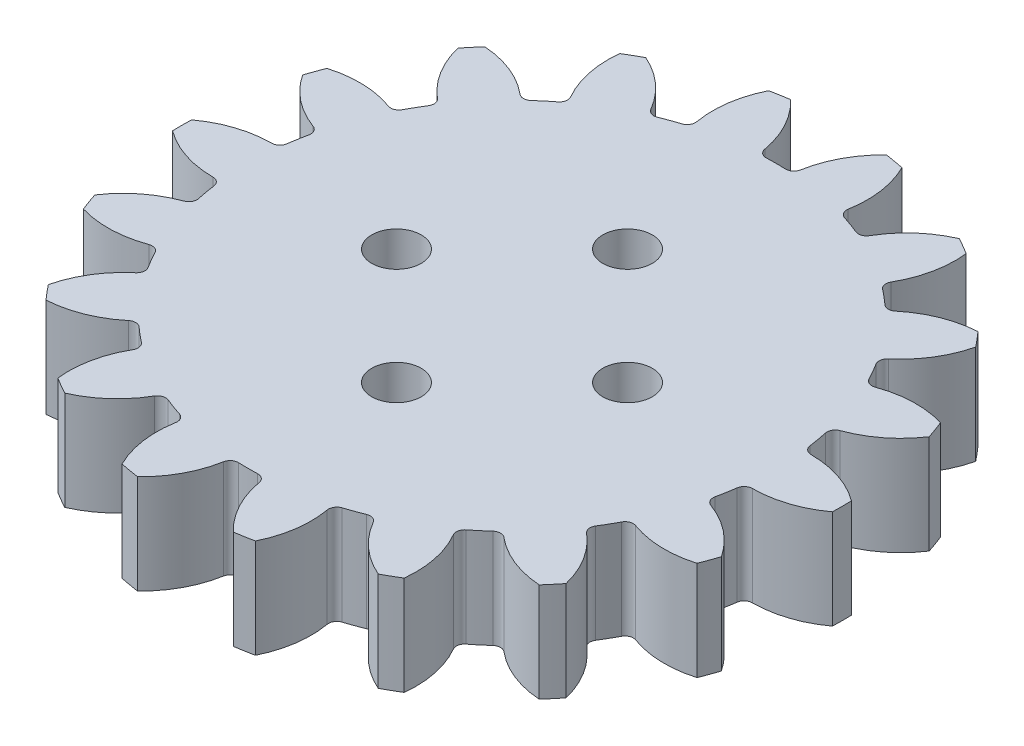
SolidWorks part; units mm, degrees
material "聚脂树脂"
ref_plane "前视基准面" through (0, 0, 0) normal (0, 0, 1) x (1, 0, 0)
ref_plane "上视基准面" through (0, 0, 0) normal (0, 1, 0) x (1, 0, 0)
ref_plane "右视基准面" through (0, 0, 0) normal (1, 0, 0) x (0, 0, -1)
other "Configuration Table"
sketch "草图1" plane through (0, 0, 0) normal (0, 1, 0) x (1, 0, 0)
  line L0 (0, 24.6773) -> (0, -25.3836) construction
  line L1 (0, 0) -> (0, 7) construction
  line L2 (0, 0) -> (7, 0) construction
  circle A0 centre (0, 0) radius 20
  circle A1 centre (0, 0) radius 7 construction
  circle A2 centre (0, 7) radius 1.5
  circle A3 centre (7, 0) radius 1.5
  circle A4 centre (0, -7) radius 1.5
  circle A5 centre (-7, 0) radius 1.5
  dimension "D1" = 40
  dimension "D2" = 14
  dimension "D3" = 3
  dimension "D5" = 90
  dimension "D4" = 4
extrude "凸台-拉伸1" add sketch "草图1" along normal blind 6
sketch "草图2" plane through (0, 0, 0) normal (0, 1, 0) x (1, 0, 0)
  line L0 (0, 34.1833) -> (0, -32.9585) construction
  line L1 (0, 0) -> (3.031, 34.644) construction
  line L2 (1.5688, 17.9315) -> (39.6443, 14.6003) construction
  line L3 (1.5688, 17.9315) -> (27.606, 5.7901) construction
  line L4 (0, 0) -> (7.1484, 15.3297) construction
  circle A0 centre (0, 0) radius 18 construction
  arc A1 (2.903, 19.7882) -> (-2.903, 19.7882) centre (0, 0) ccw
  circle A2 centre (0, 0) radius 20 construction
  arc A3 (0.5758, 15.9896) -> (-0.5758, 15.9896) centre (0, 0) ccw
  arc A4 (2.903, 19.7882) -> (1.0861, 16.4022) centre (7.1484, 15.3297) ccw
  arc A5 (1.0861, 16.4022) -> (0.5758, 15.9896) centre (0.5938, 16.4893) cw
  arc A6 (-1.0861, 16.4022) -> (-0.5758, 15.9896) centre (-0.5938, 16.4893) ccw
  arc A7 (-2.903, 19.7882) -> (-1.0861, 16.4022) centre (-7.1484, 15.3297) cw
  dimension "D2" = 36
  dimension "D4" = 16
  dimension "D5" = 0.5
  dimension "D1" = 5
  dimension "D3" = 20
extrude "切除-拉伸1" cut sketch "草图2" along normal through all and the other way through all
pattern_circular "阵列(圆周)1" count 18 over 360 about axis through (0, 0, 0) along (0, 1, 0) of "切除-拉伸1"
sketch "草图3" plane through (0, 0, 0) normal (0, 1, 0) x (1, 0, 0)
  circle A0 centre (0, 0) radius 18 construction
  dimension "D1" = 36
